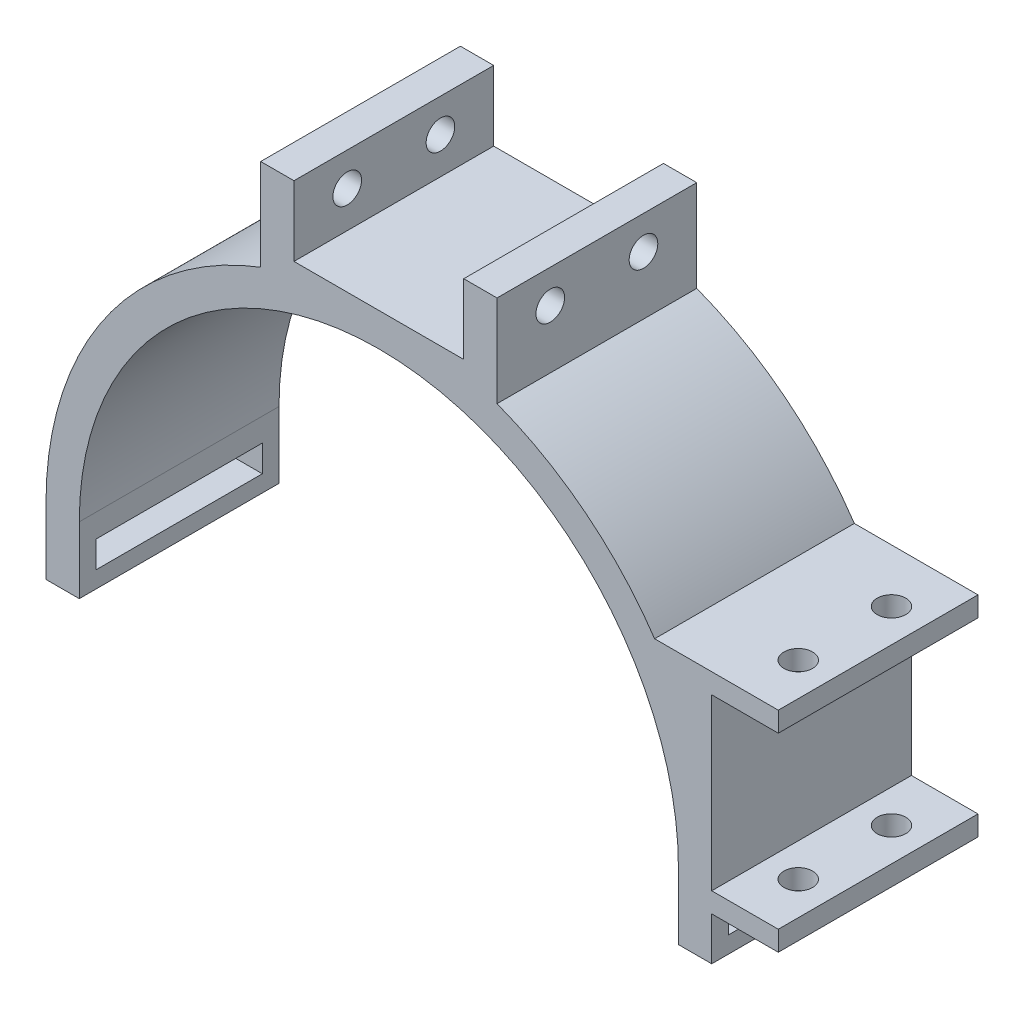
SolidWorks part; units mm, degrees
ref_plane "Front Plane" through (0, 0, 0) normal (0, 0, 1) x (1, 0, 0)
ref_plane "Top Plane" through (0, 0, 0) normal (0, 1, 0) x (1, 0, 0)
ref_plane "Right Plane" through (0, 0, 0) normal (1, 0, 0) x (0, 0, -1)
sketch "Sketch1" plane through (0, 0, 0) normal (0, 0, 1) x (1, 0, 0)
  line L0 (0, 0) -> (90, 0) construction
  line L1 (45, 45) -> (45, 0) construction
  line L2 (0, 0) -> (-5, 0)
  line L3 (90, 0) -> (95, 0)
  line L4 (45, 50) -> (45, 45) construction
  line L5 (95, -10) -> (90, -10)
  line L6 (-5, 0) -> (0, 0)
  line L7 (-5, 0) -> (-5, -10)
  line L8 (-5, -10) -> (0, -10)
  line L9 (0, 0) -> (0, -10)
  line L10 (90, 0) -> (90, -10)
  line L11 (95, 0) -> (90, 0)
  line L12 (95, 0) -> (95, -10)
  arc A0 (0, 0) -> (90, 0) centre (45, 0) cw
  arc A1 (-5, 0) -> (95, 0) centre (45, 0) cw
  dimension "D1" = 90
  dimension "D2" = 45
  dimension "D3" = 5
  dimension "D4" = 5
  dimension "D5" = 10
extrude "Boss-Extrude1" add sketch "Sketch1" along normal blind 30 contours A1 L2 A0 L3 | L12 L3 L10 L5 | L9 L2 L7 L8
sketch "Sketch2" plane through (0, 0, 30) normal (0, 0, 1) x (1, 0, 0)
  line L0 (45, 50) -> (45, 45) construction
  line L1 (57.75, 45) -> (57.75, 50)
  line L6 (57.75, 45) -> (32.25, 45)
  line L7 (45, 45) -> (45, 50)
  line L8 (57.75, 50) -> (32.25, 50)
  line L9 (32.25, 45) -> (32.25, 50)
  line L10 (32.25, 45) -> (27.25, 45)
  line L11 (32.25, 45) -> (32.25, 60.5)
  line L12 (32.25, 60.5) -> (27.25, 60.5)
  line L13 (27.25, 45) -> (27.25, 60.5)
  line L14 (57.75, 60.5) -> (62.75, 60.5)
  line L15 (62.75, 45) -> (62.75, 60.5)
  line L16 (57.75, 45) -> (62.75, 45)
  line L17 (57.75, 45) -> (57.75, 60.5)
  line L19 (27.25, 60.5) -> (62.75, 60.5)
  line L20 (27.25, 60.5) -> (27.25, 63.5)
  line L21 (27.25, 63.5) -> (62.75, 63.5)
  line L22 (62.75, 60.5) -> (62.75, 63.5)
  arc A0 (95, 0) -> (-5, 0) centre (45, 0) ccw construction
  arc A1 (90, 0) -> (0, 0) centre (45, 0) ccw construction
  arc M12 (95, 0) -> (-5, 0) centre (45, 0) ccw
  dimension "D1" = 12.75
  dimension "D2" = 5
  dimension "D3" = 10.5
  dimension "D4" = 3
extrude "Boss-Extrude2" add sketch "Sketch2" against normal blind 30 contours L13 L9 L11 L12 M12 | L9 L8 M12 | L9 L6 L7 M12 | L7 L6 L1 M12 | L1 L8 M12 | L17 L1 L15 L14 M12 | L13 L10 L9 M12 | L1 L16 L15 M12
sketch "Sketch3" plane through (95, 0, 0) normal (1, 0, 0) x (0, 0, -1)
  line L0 (0, 0) -> (0, -10) construction
  line L1 (-27.5, -3.5) -> (-2.5, -3.5)
  line L2 (-27.5, -3.5) -> (-27.5, -7.5)
  line L3 (-27.5, -7.5) -> (-2.5, -7.5)
  line L4 (-2.5, -3.5) -> (-2.5, -7.5)
  line L5 (-30, 0) -> (-30, -10) construction
  line L6 (-30, -10) -> (0, -10) construction
  dimension "D1" = 2.5
  dimension "D2" = 2.5
  dimension "D3" = 2.5
  dimension "D4" = 4
extrude "Cut-Extrude1" cut sketch "Sketch3" against normal through all
sketch "Sketch4" plane through (95, 0, 0) normal (1, 0, 0) x (0, 0, -1)
  line L0 (-2.5, -3.5) -> (0, -3.5) construction
  line L1 (0, 0) -> (0, -10) construction
  line L2 (-30, 46.7433) -> (-30, 0) construction
  line L3 (0, -3.5) -> (-30, -3.5)
  line L4 (0, -3.5) -> (0, 28)
  line L5 (0, 28) -> (-30, 28)
  line L6 (-30, -3.5) -> (-30, 28)
  dimension "D1" = 31.5
extrude "Boss-Extrude3" add sketch "Sketch4" against normal up to next
sketch "Sketch5" plane through (95, 0, 0) normal (1, 0, 0) x (0, 0, -1)
  line L0 (-2.5, -3.5) -> (0, -3.5) construction
  line L1 (0, 28) -> (0, -10) construction
  line L2 (-30, 28) -> (-30, -10) construction
  line L3 (0, -3.5) -> (-30, -3.5)
  line L4 (0, -3.5) -> (0, -0.5)
  line L5 (0, -0.5) -> (-30, -0.5)
  line L6 (-30, -3.5) -> (-30, -0.5)
  line L8 (0, 28) -> (-30, 28)
  line L9 (0, 28) -> (0, 25)
  line L10 (0, 25) -> (-30, 25)
  line L11 (-30, 28) -> (-30, 25)
  dimension "D1" = 3
  dimension "D2" = 3
extrude "Boss-Extrude4" add sketch "Sketch5" along normal blind 10
sketch "Sketch6" plane through (27.25, 0, 0) normal (-1, 0, 0) x (0, 0, 1)
  line L0 (30, 55.5) -> (0, 55.5) construction
  line L1 (30, 46.7433) -> (30, 60.5) construction
  line L2 (0, 46.7433) -> (0, 60.5) construction
  line L3 (0, 60.5) -> (30, 60.5) construction
  line L4 (15, 60.5) -> (15, 46.7433) construction
  line L5 (30, 46.7433) -> (0, 46.7433) construction
  circle A0 centre (22, 55.5) radius 2.15
  circle A1 centre (8, 55.5) radius 2.15
  dimension "D2" = 4.3
  dimension "D3" = 7
  dimension "D1" = 5
extrude "Cut-Extrude2" cut sketch "Sketch6" against normal through all
sketch "Sketch7" plane through (0, 28, 0) normal (0, 1, 0) x (1, 0, 0)
  line L0 (100, 0) -> (100, -30) construction
  line L3 (86.4246, 0) -> (105, 0) construction
  line L4 (86.4246, -30) -> (105, -30) construction
  line L5 (105, 0) -> (105, -30) construction
  line L6 (105, -15) -> (86.4246, -15) construction
  line L7 (86.4246, -30) -> (86.4246, 0) construction
  circle A0 centre (100, -22) radius 2.15
  circle A1 centre (100, -8) radius 2.15
  dimension "D2" = 4.3
  dimension "D3" = 7
  dimension "D1" = 5
extrude "Cut-Extrude3" cut sketch "Sketch7" against normal through all
